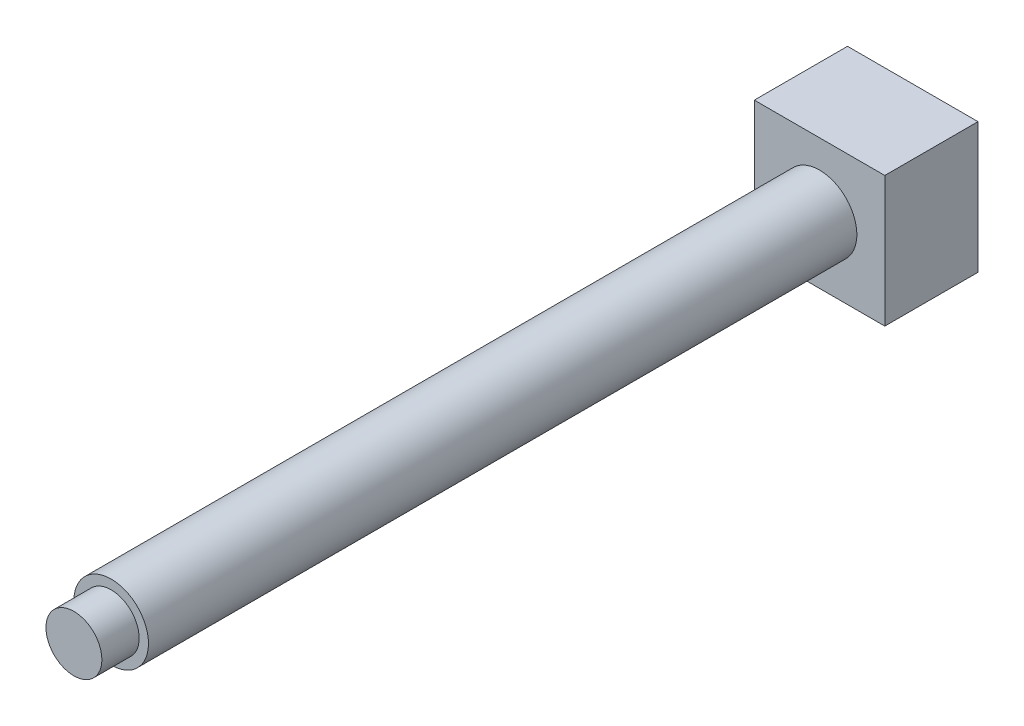
SolidWorks part; units mm, degrees
ref_plane "Front Plane" through (0, 0, 0) normal (0, 0, 1) x (1, 0, 0)
ref_plane "Top Plane" through (0, 0, 0) normal (0, 1, 0) x (1, 0, 0)
ref_plane "Right Plane" through (0, 0, 0) normal (1, 0, 0) x (0, 0, -1)
sketch "Sketch2" plane through (0, 0, 0) normal (0, 0, 1) x (1, 0, 0)
  circle A0 centre (0, 0) radius 20
  dimension "D1" = 40
extrude "Boss-Extrude2" add sketch "Sketch2" along normal blind 380
sketch "Sketch4" plane through (0, 0, 0) normal (0, 0, -1) x (-1, 0, 0)
  line L1 (35, -35) -> (-35, -35)
  line L2 (35, -35) -> (35, 35)
  line L3 (35, 35) -> (-35, 35)
  line L4 (-35, -35) -> (-35, 35)
  line L5 (35, -35) -> (-35, 35) construction
  line L6 (35, 35) -> (-35, -35) construction
  point P0 (0, 0)
  dimension "D1" = 70
  dimension "D2" = 70
extrude "Boss-Extrude3" add sketch "Sketch4" along normal blind 50
sketch "Sketch5" plane through (0, 0, 380) normal (0, 0, 1) x (1, 0, 0)
  circle A0 centre (0, 0) radius 15
extrude "Boss-Extrude4" add sketch "Sketch5" along normal blind 20
sketch "Sketch6" plane through (0, 0, 400) normal (0, 0, 1) x (1, 0, 0)
  point P0 (0, 0)
